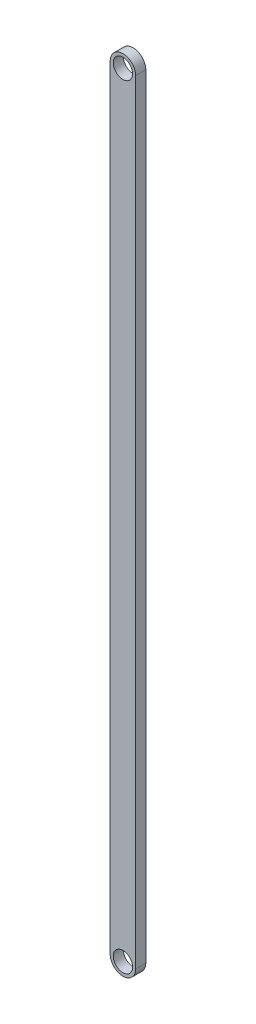
SolidWorks part; units mm, degrees
ref_plane "Front Plane" through (0, 0, 0) normal (0, 0, 1) x (1, 0, 0)
ref_plane "Top Plane" through (0, 0, 0) normal (0, 1, 0) x (1, 0, 0)
ref_plane "Right Plane" through (0, 0, 0) normal (1, 0, 0) x (0, 0, -1)
sketch "Sketch1" plane through (0, 0, 0) normal (0, 0, 1) x (1, 0, 0)
  line L0 (-4.826, 19.1972) -> (-4.826, -366.8828)
  line L1 (7.874, 19.1972) -> (7.874, -366.8828)
  arc A0 (7.874, 19.1972) -> (-4.826, 19.1972) centre (1.524, 19.1972) ccw
  arc A1 (-4.826, -366.8828) -> (7.874, -366.8828) centre (1.524, -366.8828) ccw
  circle A2 centre (1.524, 19.1972) radius 4.826
  circle A3 centre (1.524, -366.8828) radius 4.826
  dimension "D1" = 12.7
  dimension "D2" = 12.7
  dimension "D3" = 386.08
extrude "Boss-Extrude1" add sketch "Sketch1" along normal blind 5.08 contours A1 L1 A0 L0
sketch "Sketch2" plane through (0, 0, 5.08) normal (0, 0, 1) x (1, 0, 0)
  circle A0 centre (1.524, 19.1972) radius 4.826
  circle A1 centre (1.524, -366.8828) radius 4.826
extrude "Cut-Extrude1" cut sketch "Sketch2" against normal through all
